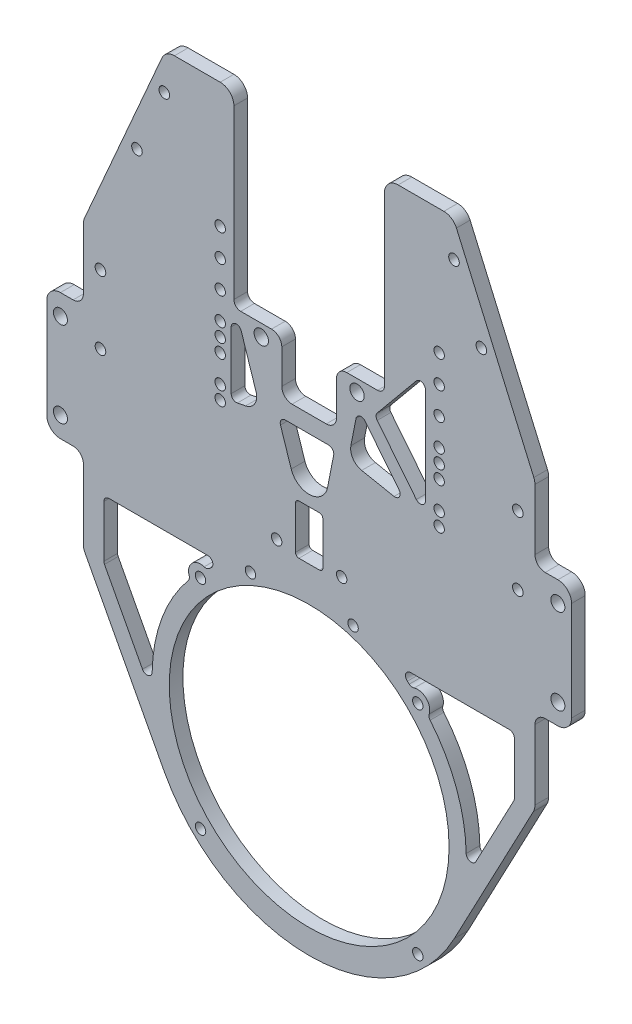
SolidWorks part; units mm, degrees
ref_plane "前视基准面" through (0, 0, 0) normal (0, 0, 1) x (1, 0, 0)
ref_plane "上视基准面" through (0, 0, 0) normal (0, 1, 0) x (1, 0, 0)
ref_plane "右视基准面" through (0, 0, 0) normal (1, 0, 0) x (0, 0, -1)
sketch "草图1" plane through (0, 0, 0) normal (0, 0, 1) x (1, 0, 0)
  line L0 (0, 0) -> (12.8351, 41.9818) construction
  line L1 (-48, 0) -> (48, 0) construction
  line L2 (-48, 0) -> (-48, 105.1) construction
  line L3 (-48, 105.1) -> (48, 105.1)
  line L4 (48, 0) -> (48, 105.1) construction
  line L5 (0, 0) -> (-17.1531, 40.4102) construction
  line L6 (0, 0) -> (0, 40.9) construction
  line L7 (-9.5, 52.6) -> (9.5, 52.6) construction
  line L8 (-42.4264, -22.4499) -> (-66, 22.1)
  line L9 (-14, 101.6) -> (14, 101.6) construction
  line L10 (-66, 22.1) -> (-66, 105.1)
  line L11 (0, 0) -> (0, 52.6) construction
  line L12 (0, 52.6) -> (0, 101.6) construction
  line L13 (-66, 105.1) -> (-48, 105.1)
  line L14 (48, 105.1) -> (66, 105.1)
  line L15 (66, 105.1) -> (66, 22.1)
  line L16 (66, 22.1) -> (42.4264, -22.4499)
  arc A0 (-42.4264, -22.4499) -> (42.4264, -22.4499) centre (0, 0) ccw
  circle A1 centre (0, 0) radius 40.9
  circle A2 centre (12.8351, 41.9818) radius 1.525
  circle A3 centre (-17.1531, 40.4102) radius 1.525
  circle A4 centre (0, 0) radius 44.9 construction
  circle A5 centre (-31.7491, 31.7491) radius 1.525
  circle A6 centre (31.7491, 31.7491) radius 1.525
  circle A7 centre (31.7491, -31.7491) radius 1.525
  circle A8 centre (-31.7491, -31.7491) radius 1.525
  circle A9 centre (-14, 101.6) radius 2.1
  circle A10 centre (14, 101.6) radius 2.1
  circle A11 centre (-9.5, 52.6) radius 1.525
  circle A12 centre (9.5, 52.6) radius 1.525
  point P24 (0, 0)
  dimension "D2" = 96
  dimension "D3" = 81.8
  dimension "D8" = 89.8
  dimension "D9" = 3.05
  dimension "D14" = 4.2
  dimension "D1" = 105.1
  dimension "D4" = 43.9
  dimension "D5" = 17
  dimension "D6" = 40
  dimension "D10" = 52.6
  dimension "D11" = 19
  dimension "D12" = 28
  dimension "D13" = 49
  dimension "D15" = 132
  dimension "D16" = 83
  dimension "D7" = 4
extrude "凸台-拉伸1" add sketch "草图1" along normal blind 4
sketch "草图3" plane through (0, 0, 4) normal (0, 0, 1) x (1, 0, 0)
  line L0 (-66, 105.1) -> (-42, 160.1)
  line L1 (-42, 160.1) -> (-22, 160.1)
  line L2 (-22, 160.1) -> (-22, 105.1)
  line L3 (66, 105.1) -> (-66, 105.1) construction
  line L4 (-22, 105.1) -> (-66, 105.1)
  line L5 (0, 105.1) -> (0, 160.1) construction
  line L6 (22, 160.1) -> (22, 105.1)
  line L7 (42, 160.1) -> (22, 160.1)
  line L8 (66, 105.1) -> (42, 160.1)
  line L9 (22, 105.1) -> (66, 105.1)
  dimension "D1" = 44
  dimension "D2" = 55
  dimension "D3" = 20
extrude "凸台-拉伸2" add sketch "草图3" against normal up to surface (4 mm away) up to face at (0, 30.6583, 0)
sketch "草图2" plane through (0, 0, 4) normal (0, 0, 1) x (1, 0, 0)
  line L0 (0, 52.6) -> (0, 91.6) construction
  line L1 (38, 83.6) -> (-26, 83.6) construction
  line L2 (38, 83.6) -> (38, 99.6) construction
  line L3 (38, 99.6) -> (-26, 99.6) construction
  line L4 (-26, 83.6) -> (-26, 99.6) construction
  line L5 (38, 83.6) -> (-26, 99.6) construction
  line L6 (38, 99.6) -> (-26, 83.6) construction
  line L7 (0, 52.6) -> (0, 101.6) construction
  line L8 (0, 91.6) -> (6, 91.6) construction
  circle A0 centre (38, 99.6) radius 1.525
  circle A1 centre (38, 83.6) radius 1.525
  circle A2 centre (-26, 99.6) radius 1.525
  circle A3 centre (-26, 83.6) radius 1.525
  circle A4 centre (38, 107.6) radius 1.525
  circle A5 centre (38, 91.6) radius 1.525
  circle A6 centre (-26, 107.6) radius 1.525
  circle A7 centre (-26, 91.6) radius 1.525
  circle A8 centre (-26, 95.6) radius 1.525
  circle A9 centre (-26, 79.6) radius 1.525
  circle A10 centre (38, 95.6) radius 1.525
  circle A11 centre (38, 79.6) radius 1.525
  circle A12 centre (38, 115.6) radius 1.525
  circle A13 centre (-26, 115.6) radius 1.525
  circle A14 centre (38, 123.6) radius 1.525
  circle A15 centre (-26, 123.6) radius 1.525
  point P0 (6, 91.6)
  dimension "D5" = 3.05
  dimension "D7" = 8
  dimension "D9" = 4
  dimension "D11" = 8
  dimension "D1" = 16
  dimension "D2" = 64
  dimension "D3" = 39
  dimension "D4" = 6
  dimension "D6" = 2
  dimension "D8" = 2
  dimension "D10" = 3
extrude "切除-拉伸1" cut sketch "草图2" against normal blind 10
sketch "草图4" plane through (0, 0, 4) normal (0, 0, 1) x (1, 0, 0)
  line L0 (-66, 105.1) -> (-61, 105.1) construction
  line L1 (-61, 105.1) -> (-61, 95.1) construction
  line L2 (-61, 95.1) -> (-61, 75.1) construction
  line L3 (-42, 160.1) -> (-38.3338, 158.5002) construction
  line L4 (-38.3338, 158.5002) -> (-42.3333, 149.3348) construction
  line L5 (-42.3333, 149.3348) -> (-50.3322, 131.004) construction
  line L7 (-42, 160.1) -> (-66, 105.1) construction
  line L8 (0, 105.1) -> (0, 145.1) construction
  line L9 (22, 105.1) -> (-22, 105.1) construction
  circle A0 centre (-61, 95.1) radius 1.55
  circle A1 centre (-61, 75.1) radius 1.55
  circle A2 centre (-42.3333, 149.3348) radius 1.55
  circle A3 centre (-50.3322, 131.004) radius 1.55
  circle A4 centre (61, 75.1) radius 1.55
  circle A5 centre (61, 95.1) radius 1.55
  circle A6 centre (50.3322, 131.004) radius 1.55
  circle A7 centre (42.3333, 149.3348) radius 1.55
  dimension "D5" = 3.1
  dimension "D1" = 5
  dimension "D2" = 10
  dimension "D3" = 20
  dimension "D4" = 10
  dimension "D6" = 4
extrude "切除-拉伸2" cut sketch "草图4" against normal blind 10
sketch "草图5" plane through (0, 0, 4) normal (0, 0, 1) x (1, 0, 0)
  line L0 (22, 105.1) -> (-22, 105.1) construction
  line L1 (-8, 105.1) -> (8, 105.1)
  line L2 (-8, 105.1) -> (-8, 92.1)
  line L3 (-5, 89.1) -> (5, 89.1)
  line L4 (8, 105.1) -> (8, 92.1)
  arc A0 (-8, 92.1) -> (-5, 89.1) centre (-5, 92.1) ccw
  arc A1 (5, 89.1) -> (8, 92.1) centre (5, 92.1) ccw
  point P6 (0, 105.1)
  point P11 (8, 89.1)
  dimension "D3" = 3
  dimension "D1" = 16
  dimension "D2" = 16
extrude "切除-拉伸3" cut sketch "草图5" against normal blind 10
sketch "草图6" plane through (0, 0, 4) normal (0, 0, 1) x (1, 0, 0)
  line L0 (-66, 105.1) -> (-66, 22.1) construction
  line L1 (-66, 83.5) -> (-72.7, 83.5)
  line L2 (-66, 83.5) -> (-66, 46.5)
  line L3 (-66, 46.5) -> (-72.7, 46.5)
  line L4 (-76.7, 79.5) -> (-76.7, 50.5)
  line L5 (0, 0) -> (0, 40.9) construction
  line L6 (-72.7, 83.5) -> (-72.7, 77.5) construction
  line L7 (-72.7, 77.5) -> (-72.7, 52.5) construction
  line L8 (-72.7, 52.5) -> (-72.7, 46.5) construction
  line L9 (66, 46.5) -> (72.7, 46.5)
  line L10 (76.7, 79.5) -> (76.7, 50.5)
  line L11 (66, 83.5) -> (72.7, 83.5)
  line L12 (66, 83.5) -> (66, 46.5)
  circle A0 centre (0, 0) radius 40.9 construction
  circle A1 centre (-72.7, 77.5) radius 2.05
  circle A2 centre (-72.7, 52.5) radius 2.05
  arc A5 (-72.7, 83.5) -> (-76.7, 79.5) centre (-72.7, 79.5) ccw
  arc A6 (-72.7, 46.5) -> (-76.7, 50.5) centre (-72.7, 50.5) cw
  circle A7 centre (72.7, 52.5) radius 2.05
  circle A8 centre (72.7, 77.5) radius 2.05
  arc A9 (72.7, 46.5) -> (76.7, 50.5) centre (72.7, 50.5) ccw
  arc A10 (72.7, 83.5) -> (76.7, 79.5) centre (72.7, 79.5) cw
  point P25 (-72.7, 65)
  point P28 (-76.7, 83.5)
  point P31 (-76.7, 46.5)
  dimension "D5" = 4.1
  dimension "D7" = 4
  dimension "D1" = 10.7
  dimension "D2" = 4
  dimension "D3" = 6
  dimension "D4" = 25
  dimension "D6" = 65
extrude "凸台-拉伸3" add sketch "草图6" against normal up to surface (4 mm away) up to face at (0, 89.2171, 0)
fillet "圆角1" radius 3 6 edges at (-8, 105.1, 2) (8, 105.1, 2) (66, 46.5, 2) (66, 83.5, 2) (-66, 83.5, 2) (-66, 46.5, 2)
fillet "圆角2" radius 2 2 edges at (-22, 105.1, 2) (22, 105.1, 2)
fillet "圆角3" radius 4 8 edges at (66, 22.1, 2) (-66, 22.1, 2) (-66, 105.1, 2) (-42, 160.1, 2) (-22, 160.1, 2) (22, 160.1, 2) (42, 160.1, 2) (66, 105.1, 2)
sketch "草图7" plane through (0, 0, 4) normal (0, 0, 1) x (1, 0, 0)
  line L0 (59.5, 98.1) -> (42.5, 98.1) construction
  line L1 (41, 99.6) -> (41, 125.1) construction
  line L2 (39.5, 126.6) -> (28.5, 126.6) construction
  line L3 (27, 128.1) -> (27, 154.6) construction
  line L4 (28.5, 156.1) -> (37.8333, 156.1) construction
  line L5 (39.3333, 154.6) -> (39.3333, 147.8348) construction
  line L6 (40.8333, 146.3348) -> (42.6603, 146.3348) construction
  line L7 (44.0351, 145.4347) -> (47.207, 138.1659) construction
  line L8 (47.3322, 137.566) -> (47.3322, 129.504) construction
  line L9 (48.8322, 128.004) -> (50.6592, 128.004) construction
  line L10 (52.034, 127.104) -> (60.8748, 106.8438) construction
  line L11 (61, 106.2439) -> (61, 99.6) construction
  line L12 (22, 156.1) -> (22, 107.1) construction
  line L13 (39.3812, 160.1) -> (26, 160.1) construction
  line L14 (65.6662, 105.8651) -> (43.0474, 157.6998) construction
  line L15 (66, 86.5) -> (66, 104.2653) construction
  line L16 (60.5, 78.1) -> (59.5, 78.1) construction
  line L17 (58, 76.6) -> (58, 75.9804) construction
  line L18 (56.212, 74.5083) -> (42.212, 77.2475) construction
  line L19 (41, 78.7196) -> (41, 91.6) construction
  line L20 (42.5, 93.1) -> (56.7218, 93.1) construction
  line L21 (57.7825, 92.6607) -> (61.5607, 88.8825) construction
  line L22 (62, 87.8218) -> (62, 79.6) construction
  line L23 (11.8206, 51.8859) -> (9.0933, 60.569) construction
  line L24 (22.846, 75.9417) -> (56.576, 69.3423) construction
  line L25 (59, 66.3981) -> (59, 47.4818) construction
  line L26 (55, 43.4818) -> (23.2692, 43.4818) construction
  line L27 (76.7, 50.5) -> (76.7, 79.5) construction
  line L28 (60, 36.9818) -> (60, 21.8239)
  line L29 (59.8258, 21.1224) -> (48.7185, 0.1315)
  line L30 (58.5, 38.4818) -> (29.6498, 38.4818)
  line L31 (66, 23.0931) -> (66, 43.5) construction
  line L32 (42.4264, -22.4499) -> (65.5355, 21.2222) construction
  line L33 (0, 0) -> (0, -40.9) construction
  line L34 (-58.5, 38.4818) -> (-29.6498, 38.4818)
  line L35 (-59.8258, 21.1224) -> (-48.7185, 0.1315)
  line L36 (-60, 36.9818) -> (-60, 21.8239)
  line L37 (-55, 43.4818) -> (-23.2692, 43.4818) construction
  line L38 (-59, 66.3981) -> (-59, 47.4818) construction
  line L39 (-22.846, 75.9417) -> (-56.576, 69.3423) construction
  line L40 (-11.8206, 51.8859) -> (-9.0933, 60.569) construction
  line L41 (-62, 87.8218) -> (-62, 79.6) construction
  line L42 (-57.7825, 92.6607) -> (-61.5607, 88.8825) construction
  line L43 (-42.5, 93.1) -> (-56.7218, 93.1) construction
  line L44 (-41, 78.7196) -> (-41, 91.6) construction
  line L45 (-56.212, 74.5083) -> (-42.212, 77.2475) construction
  line L46 (-58, 76.6) -> (-58, 75.9804) construction
  line L47 (-60.5, 78.1) -> (-59.5, 78.1) construction
  line L48 (-61, 106.2439) -> (-61, 99.6) construction
  line L49 (-52.034, 127.104) -> (-60.8748, 106.8438) construction
  line L50 (-48.8322, 128.004) -> (-50.6592, 128.004) construction
  line L51 (-47.3322, 137.566) -> (-47.3322, 129.504) construction
  line L52 (-44.0351, 145.4347) -> (-47.207, 138.1659) construction
  line L53 (-40.8333, 146.3348) -> (-42.6603, 146.3348) construction
  line L54 (-39.3333, 154.6) -> (-39.3333, 147.8348) construction
  line L55 (-28.5, 156.1) -> (-37.8333, 156.1) construction
  line L56 (-27, 128.1) -> (-27, 154.6) construction
  line L57 (-39.5, 126.6) -> (-28.5, 126.6) construction
  line L58 (-41, 99.6) -> (-41, 125.1) construction
  line L59 (-59.5, 98.1) -> (-42.5, 98.1) construction
  line L60 (24.8079, 80.6526) -> (15.3559, 82.5019)
  line L61 (12.1985, 87.1962) -> (13.693, 94.8284)
  line L62 (16.3364, 95.4771) -> (26.2673, 83.0617)
  line L64 (31.3286, 83.1377) -> (19.891, 97.4369)
  line L65 (19.9057, 99.3289) -> (31.3433, 113.1817)
  line L66 (34, 112.2267) -> (34, 84.0747)
  line L67 (-42.212, 77.2475) -> (-30.212, 79.5953) construction
  line L68 (-29, 81.0674) -> (-29, 91.6) construction
  line L69 (-30.5, 93.1) -> (-42.5, 93.1) construction
  line L71 (-42.5, 98.1) -> (-30.5, 98.1) construction
  line L72 (-29, 99.6) -> (-29, 126.6) construction
  line L73 (-29, 126.6) -> (-28.5, 126.6) construction
  line L74 (-18.5719, 81.8727) -> (-21.0016, 81.3973)
  line L75 (-22.7897, 82.8694) -> (-22.7897, 99.76)
  line L76 (-19.8644, 100.2276) -> (-15.5393, 87.0453)
  line L77 (5.3831, 73.2062) -> (7.1661, 82.3118)
  line L78 (5.694, 84.1) -> (-6.9596, 84.1)
  line L79 (-8.3848, 82.1324) -> (-5.2403, 72.5485)
  line L80 (-5, 89.1) -> (5, 89.1) construction
  circle A0 centre (38, 123.6) radius 1.525 construction
  circle A1 centre (42.3333, 149.3348) radius 1.55 construction
  circle A2 centre (50.3322, 131.004) radius 1.55 construction
  circle A3 centre (61, 95.1) radius 1.55 construction
  arc A4 (60.8748, 106.8438) -> (61, 106.2439) centre (59.5, 106.2439) cw construction
  arc A5 (50.6592, 128.004) -> (52.034, 127.104) centre (50.6592, 126.504) cw construction
  arc A6 (47.3322, 129.504) -> (48.8322, 128.004) centre (48.8322, 129.504) ccw construction
  arc A7 (47.207, 138.1659) -> (47.3322, 137.566) centre (45.8322, 137.566) cw construction
  arc A8 (39.3333, 147.8348) -> (40.8333, 146.3348) centre (40.8333, 147.8348) ccw construction
  arc A9 (37.8333, 156.1) -> (39.3333, 154.6) centre (37.8333, 154.6) cw construction
  arc A10 (42.6603, 146.3348) -> (44.0351, 145.4347) centre (42.6603, 144.8348) cw construction
  arc A11 (28.5, 126.6) -> (27, 128.1) centre (28.5, 128.1) cw construction
  arc A12 (41, 125.1) -> (39.5, 126.6) centre (39.5, 125.1) ccw construction
  arc A13 (27, 154.6) -> (28.5, 156.1) centre (28.5, 154.6) cw construction
  arc A14 (42.5, 98.1) -> (41, 99.6) centre (42.5, 99.6) cw construction
  arc A15 (59.5, 98.1) -> (61, 99.6) centre (59.5, 99.6) ccw construction
  circle A16 centre (61, 75.1) radius 1.55 construction
  circle A17 centre (38, 79.6) radius 1.525 construction
  arc A19 (61.5607, 88.8825) -> (62, 87.8218) centre (60.5, 87.8218) cw construction
  arc A20 (56.7218, 93.1) -> (57.7825, 92.6607) centre (56.7218, 91.6) cw construction
  arc A21 (41, 91.6) -> (42.5, 93.1) centre (42.5, 91.6) cw construction
  arc A22 (42.212, 77.2475) -> (41, 78.7196) centre (42.5, 78.7196) cw construction
  arc A23 (58, 75.9804) -> (56.212, 74.5083) centre (56.5, 75.9804) cw construction
  arc A24 (59.5, 78.1) -> (58, 76.6) centre (59.5, 76.6) ccw construction
  arc A25 (60.5, 78.1) -> (62, 79.6) centre (60.5, 79.6) ccw construction
  arc A26 (59, 47.4818) -> (55, 43.4818) centre (55, 47.4818) cw construction
  arc A27 (9.0933, 60.569) -> (22.846, 75.9417) centre (20.5419, 64.165) cw construction
  arc A28 (11.8206, 51.8859) -> (23.2692, 43.4818) centre (23.2692, 55.4818) ccw construction
  arc A29 (56.576, 69.3423) -> (59, 66.3981) centre (56, 66.3981) cw construction
  circle A30 centre (12.8351, 41.9818) radius 1.525 construction
  circle A31 centre (9.5, 52.6) radius 1.525 construction
  arc A32 (29.2702, 35.3563) -> (28.7115, 35.8115) centre (0, 0) ccw
  circle A33 centre (0, 0) radius 40.9 construction
  arc A34 (35.0829, 30.6834) -> (30.6834, 35.0829) centre (31.7491, 31.7491) ccw
  arc A35 (45.8929, 0.8067) -> (35.3563, 29.2702) centre (0, 0) ccw
  arc A36 (29.6498, 38.4818) -> (28.7115, 35.8115) centre (29.6498, 36.9818) ccw
  arc A37 (48.7185, 0.1315) -> (45.8929, 0.8067) centre (47.3927, 0.833) cw
  arc A38 (35.0829, 30.6834) -> (35.3563, 29.2702) centre (36.5117, 30.2267) ccw
  arc A39 (30.6834, 35.0829) -> (29.2702, 35.3563) centre (30.2267, 36.5117) cw
  arc A40 (60, 21.8239) -> (59.8258, 21.1224) centre (58.5, 21.8239) cw
  arc A41 (60, 36.9818) -> (58.5, 38.4818) centre (58.5, 36.9818) ccw
  arc A42 (-60, 36.9818) -> (-58.5, 38.4818) centre (-58.5, 36.9818) cw
  arc A43 (-60, 21.8239) -> (-59.8258, 21.1224) centre (-58.5, 21.8239) ccw
  arc A44 (-30.6834, 35.0829) -> (-29.2702, 35.3563) centre (-30.2267, 36.5117) ccw
  arc A45 (-35.0829, 30.6834) -> (-35.3563, 29.2702) centre (-36.5117, 30.2267) cw
  arc A46 (-48.7185, 0.1315) -> (-45.8929, 0.8067) centre (-47.3927, 0.833) ccw
  arc A47 (-29.6498, 38.4818) -> (-28.7115, 35.8115) centre (-29.6498, 36.9818) cw
  arc A48 (-45.8929, 0.8067) -> (-35.3563, 29.2702) centre (0, 0) cw
  arc A49 (-35.0829, 30.6834) -> (-30.6834, 35.0829) centre (-31.7491, 31.7491) cw
  arc A50 (-29.2702, 35.3563) -> (-28.7115, 35.8115) centre (0, 0) cw
  arc A51 (-56.576, 69.3423) -> (-59, 66.3981) centre (-56, 66.3981) ccw construction
  arc A52 (-11.8206, 51.8859) -> (-23.2692, 43.4818) centre (-23.2692, 55.4818) cw construction
  arc A53 (-9.0933, 60.569) -> (-22.846, 75.9417) centre (-20.5419, 64.165) ccw construction
  arc A54 (-59, 47.4818) -> (-55, 43.4818) centre (-55, 47.4818) ccw construction
  arc A55 (-60.5, 78.1) -> (-62, 79.6) centre (-60.5, 79.6) cw construction
  arc A56 (-59.5, 78.1) -> (-58, 76.6) centre (-59.5, 76.6) cw construction
  arc A57 (-58, 75.9804) -> (-56.212, 74.5083) centre (-56.5, 75.9804) ccw construction
  arc A58 (-42.212, 77.2475) -> (-41, 78.7196) centre (-42.5, 78.7196) ccw construction
  arc A59 (-41, 91.6) -> (-42.5, 93.1) centre (-42.5, 91.6) ccw construction
  arc A60 (-56.7218, 93.1) -> (-57.7825, 92.6607) centre (-56.7218, 91.6) ccw construction
  arc A61 (-61.5607, 88.8825) -> (-62, 87.8218) centre (-60.5, 87.8218) ccw construction
  arc A62 (-59.5, 98.1) -> (-61, 99.6) centre (-59.5, 99.6) cw construction
  arc A63 (-42.5, 98.1) -> (-41, 99.6) centre (-42.5, 99.6) ccw construction
  arc A64 (-27, 154.6) -> (-28.5, 156.1) centre (-28.5, 154.6) ccw construction
  arc A65 (-41, 125.1) -> (-39.5, 126.6) centre (-39.5, 125.1) cw construction
  arc A66 (-28.5, 126.6) -> (-27, 128.1) centre (-28.5, 128.1) ccw construction
  arc A67 (-42.6603, 146.3348) -> (-44.0351, 145.4347) centre (-42.6603, 144.8348) ccw construction
  arc A68 (-37.8333, 156.1) -> (-39.3333, 154.6) centre (-37.8333, 154.6) ccw construction
  arc A69 (-39.3333, 147.8348) -> (-40.8333, 146.3348) centre (-40.8333, 147.8348) cw construction
  arc A70 (-47.207, 138.1659) -> (-47.3322, 137.566) centre (-45.8322, 137.566) ccw construction
  arc A71 (-47.3322, 129.504) -> (-48.8322, 128.004) centre (-48.8322, 129.504) cw construction
  arc A72 (-50.6592, 128.004) -> (-52.034, 127.104) centre (-50.6592, 126.504) ccw construction
  arc A73 (-60.8748, 106.8438) -> (-61, 106.2439) centre (-59.5, 106.2439) ccw construction
  circle A74 centre (38, 95.6) radius 1.525 construction
  circle A75 centre (14, 101.6) radius 2.1 construction
  arc A76 (15.3559, 82.5019) -> (12.1985, 87.1962) centre (16.1239, 86.4275) cw
  arc A77 (31.3433, 113.1817) -> (34, 112.2267) centre (32.5, 112.2267) cw
  arc A78 (19.891, 97.4369) -> (19.9057, 99.3289) centre (21.0624, 98.3739) cw
  arc A79 (34, 84.0747) -> (31.3286, 83.1377) centre (32.5, 84.0747) cw
  arc A80 (13.693, 94.8284) -> (16.3364, 95.4771) centre (15.1651, 94.5402) cw
  arc A81 (24.8079, 80.6526) -> (26.2673, 83.0617) centre (25.0959, 82.1247) ccw
  circle A82 centre (-26, 99.6) radius 1.525 construction
  arc A83 (-30.5, 98.1) -> (-29, 99.6) centre (-30.5, 99.6) ccw construction
  arc A84 (-30.212, 79.5953) -> (-29, 81.0674) centre (-30.5, 81.0674) ccw construction
  arc A85 (-29, 91.6) -> (-30.5, 93.1) centre (-30.5, 91.6) ccw construction
  circle A86 centre (-26, 91.6) radius 1.525 construction
  circle A87 centre (-9.5, 52.6) radius 1.525 construction
  circle A88 centre (-14, 101.6) radius 2.1 construction
  arc A89 (7.1661, 82.3118) -> (5.694, 84.1) centre (5.694, 82.6) ccw
  arc A90 (-6.9596, 84.1) -> (-8.3848, 82.1324) centre (-6.9596, 82.6) ccw
  arc A91 (5.3831, 73.2062) -> (-5.2403, 72.5485) centre (-0.0144, 74.2631) cw
  arc A92 (-22.7897, 99.76) -> (-19.8644, 100.2276) centre (-21.2897, 99.76) cw
  arc A93 (-21.0016, 81.3973) -> (-22.7897, 82.8694) centre (-21.2897, 82.8694) cw
  arc A94 (-18.5719, 81.8727) -> (-15.5393, 87.0453) centre (-19.3399, 85.7983) ccw
  point P117 (45.5167, -5.9193)
  dimension "D5" = 3
  dimension "D9" = 3
  dimension "D13" = 1.5
  dimension "D18" = 1.5
  dimension "D22" = 1.5
  dimension "D23" = 4
  dimension "D24" = 12
  dimension "D25" = 3
  dimension "D28" = 2
  dimension "D29" = 2
  dimension "D30" = 1.5
  dimension "D31" = 5
  dimension "D32" = 7
  dimension "D36" = 1.5
  dimension "D43" = 1.5
  dimension "D46" = 4
  dimension "D48" = 1.5
  dimension "D56" = 1.5
  dimension "D57" = 5.5
  dimension "D58" = 1.5
  dimension "D1" = 5
  dimension "D2" = 3
  dimension "D3" = 3
  dimension "D4" = 4
  dimension "D6" = 3
  dimension "D7" = 4
  dimension "D8" = 3
  dimension "D10" = 4
  dimension "D11" = 5
  dimension "D12" = 3
  dimension "D14" = 4
  dimension "D15" = 3
  dimension "D16" = 3
  dimension "D17" = 1.5
  dimension "D19" = 4
  dimension "D20" = 5
  dimension "D21" = 45
  dimension "D26" = 17.7
  dimension "D27" = 5
  dimension "D33" = 5
  dimension "D34" = 6
  dimension "D35" = 5
  dimension "D37" = 4
  dimension "D38" = 4
  dimension "D39" = 5
  dimension "D40" = 4
  dimension "D41" = 1
  dimension "D42" = 6
  dimension "D44" = 3
  dimension "D45" = 2
  dimension "D47" = 3
  dimension "D49" = 5
  dimension "D50" = 3.2103
  dimension "D51" = 5.2663
  dimension "D52" = 4
  dimension "D53" = 5
  dimension "D54" = 6
  dimension "D55" = 5
extrude "切除-拉伸4" cut sketch "草图7" against normal blind 10
sketch "草图8" plane through (0, 0, 4) normal (0, 0, 1) x (1, 0, 0)
  line L0 (0, 51.1) -> (0, 0) construction
  line L1 (-3, 51.1) -> (3, 51.1)
  line L2 (-4, 52.1) -> (-4, 64.6)
  line L3 (-3, 65.6) -> (3, 65.6)
  line L4 (4, 52.1) -> (4, 64.6)
  arc A0 (3, 51.1) -> (4, 52.1) centre (3, 52.1) ccw
  arc A1 (-4, 64.6) -> (-3, 65.6) centre (-3, 64.6) cw
  arc A2 (3, 65.6) -> (4, 64.6) centre (3, 64.6) cw
  arc A3 (-3, 51.1) -> (-4, 52.1) centre (-3, 52.1) cw
  point P9 (4, 51.1)
  point P14 (4, 65.6)
  point P17 (-4, 51.1)
  dimension "D3" = 1
  dimension "D1" = 14.5
  dimension "D2" = 8
  dimension "D4" = 51.1
extrude "切除-拉伸5" cut sketch "草图8" against normal blind 10
